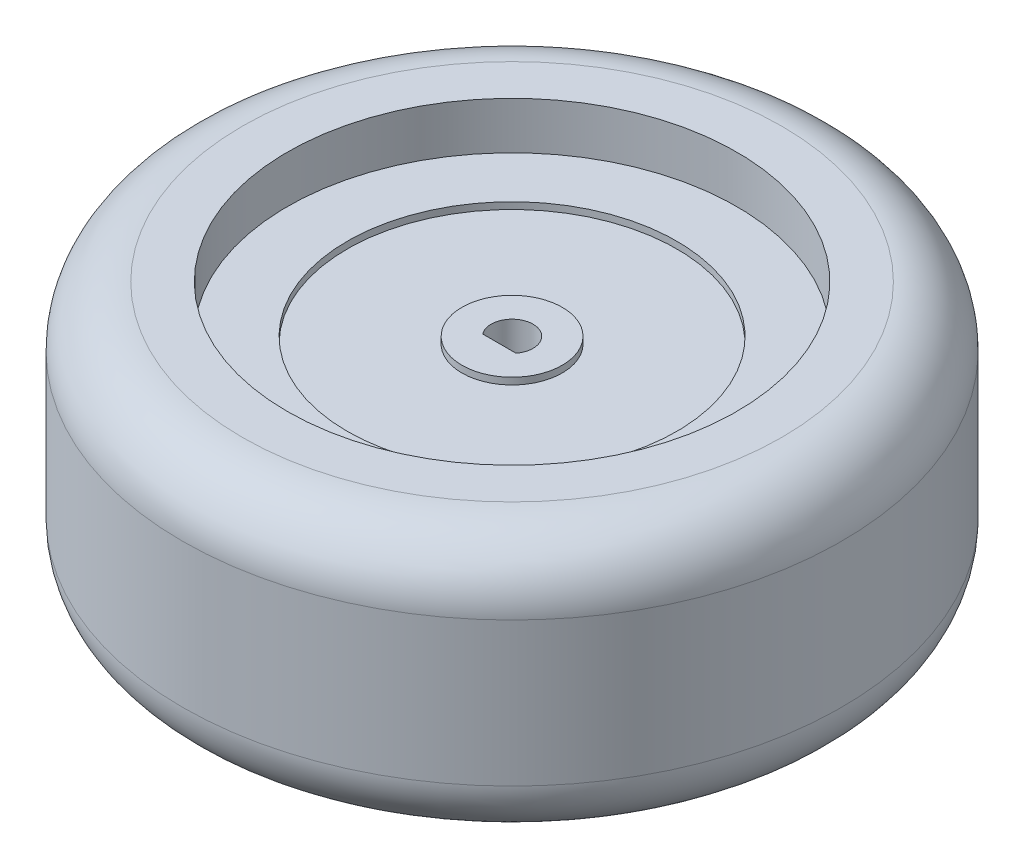
SolidWorks part; units mm, degrees
ref_plane "Front Plane" through (0, 0, 0) normal (0, 0, 1) x (1, 0, 0)
ref_plane "Top Plane" through (0, 0, 0) normal (0, 1, 0) x (1, 0, 0)
ref_plane "Right Plane" through (0, 0, 0) normal (1, 0, 0) x (0, 0, -1)
sketch "Sketch1" plane through (0, 0, 0) normal (0, 1, 0) x (1, 0, 0)
  circle A0 centre (0, 0) radius 22
  dimension "D1" = 44
extrude "Boss-Extrude1" add sketch "Sketch1" along normal blind 17.6
sketch "Sketch2" plane through (0, 17.6, 0) normal (0, 1, 0) x (1, 0, 0)
  circle A0 centre (0, 0) radius 15
  dimension "D1" = 30
extrude "Cut-Extrude1" cut sketch "Sketch2" against normal blind 3.6
sketch "Sketch3" plane through (0, 14, 0) normal (0, 1, 0) x (1, 0, 0)
  line L0 (0, -3.35) -> (0, -0.85) construction
  line L1 (-1.1124, -0.85) -> (1.1124, -0.85)
  circle A0 centre (0, 0) radius 1.4
  circle A1 centre (0, 0) radius 3.35
  point P8 (0, -0.85)
  dimension "D1" = 2.8
  dimension "D2" = 6.7
  dimension "D3" = 2.5
extrude "Cut-Extrude2" cut sketch "Sketch3" against normal blind 37.18 contours L1 A0
sketch "Sketch4" plane through (0, 14, 0) normal (0, 1, 0) x (1, 0, 0)
  line L0 (-1.1124, -0.85) -> (1.1124, -0.85)
  circle A0 centre (0, 0) radius 1.4
  circle A1 centre (0, 0) radius 3.35
  circle A2 centre (0, 0) radius 11
  circle A3 centre (0, 0) radius 15
  line M2 (1.1124, -0.85) -> (-1.1124, -0.85)
  arc M3 (-1.1124, -0.85) -> (1.1124, -0.85) centre (0, 0) cw
  circle M4 centre (0, 0) radius 15
  dimension "D1" = 6.7
  dimension "D2" = 22
extrude "Boss-Extrude2" add sketch "Sketch4" along normal blind 0.45 contours A1 A0 M3 | A0 M2 | A2 M4
sketch "Sketch5" plane through (0, 0, 0) normal (0, -1, 0) x (1, 0, 0)
  circle A0 centre (0, 0) radius 10.75
  dimension "D1" = 21.5
extrude "Cut-Extrude3" cut sketch "Sketch5" against normal blind 9
fillet "Fillet1" radius 4 2 edges at (0, 17.6, 22) (0, 0, 22)
sketch "Sketch6" plane through (0, 14.45, 0) normal (0, 1, 0) x (1, 0, 0)
  circle A0 centre (0, 0) radius 15
  circle A1 centre (0, 0) radius 22
  dimension "D1" = 7
